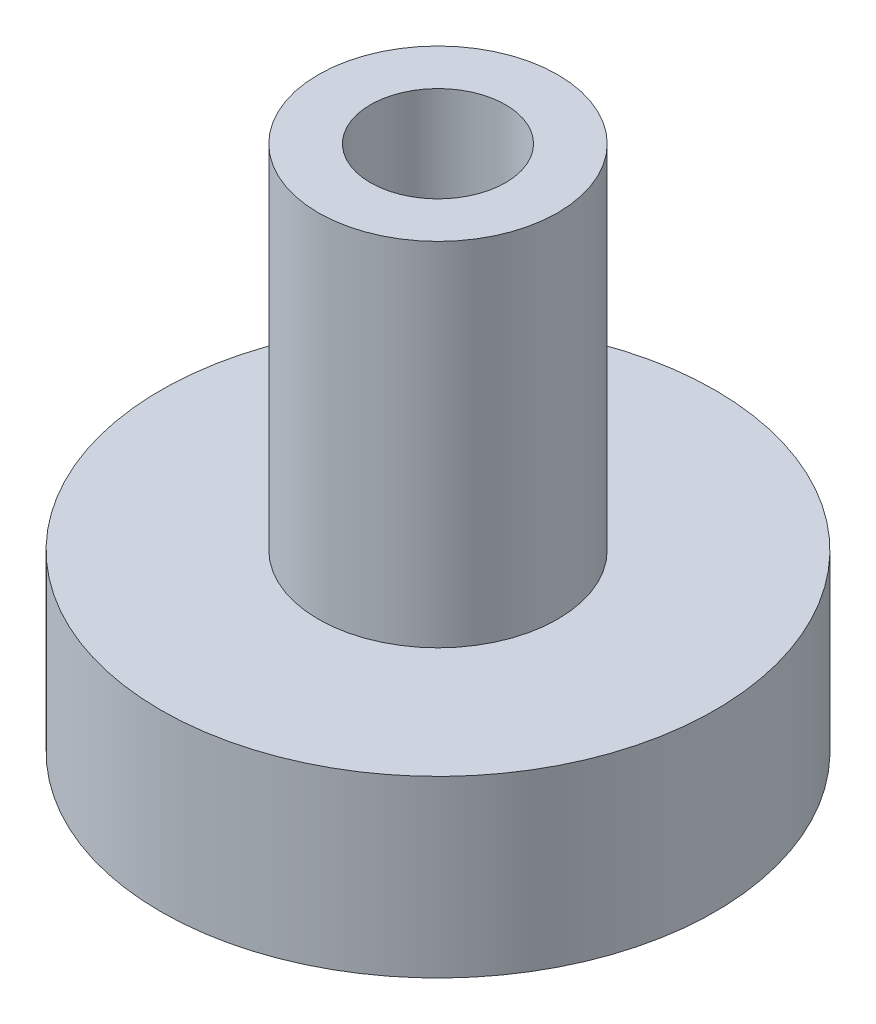
SolidWorks part; units mm, degrees
ref_plane "Front Plane" through (0, 0, 0) normal (0, 0, 1) x (1, 0, 0)
ref_plane "Top Plane" through (0, 0, 0) normal (0, 1, 0) x (1, 0, 0)
ref_plane "Right Plane" through (0, 0, 0) normal (1, 0, 0) x (0, 0, -1)
sketch "Sketch1" plane through (0, 0, 0) normal (0, 0, 1) x (1, 0, 0)
  line L0 (0, 0) -> (-2.159, 0)
  line L1 (-2.159, 0) -> (-2.159, -6.35)
  line L2 (-2.159, -6.35) -> (-5, -6.35)
  line L3 (-5, -6.35) -> (-5, -9.5)
  line L4 (-5, -9.5) -> (0, -9.5)
  line L5 (0, -9.5) -> (0, 0) construction
  line L6 (0, 0) -> (0, -9.5)
  dimension "D1" = 10
  dimension "D2" = 3.15
  dimension "D3" = 4.318
  dimension "D4" = 6.35
revolve "Revolve1" add sketch "Sketch1" angle 360 about L5
sketch "Sketch2" plane through (0, 0, 0) normal (0, 1, 0) x (1, 0, 0)
  circle A0 centre (0, 0) radius 1.2192
  dimension "D1" = 2.4384
extrude "Cut-Extrude1" cut sketch "Sketch2" against normal up to next
